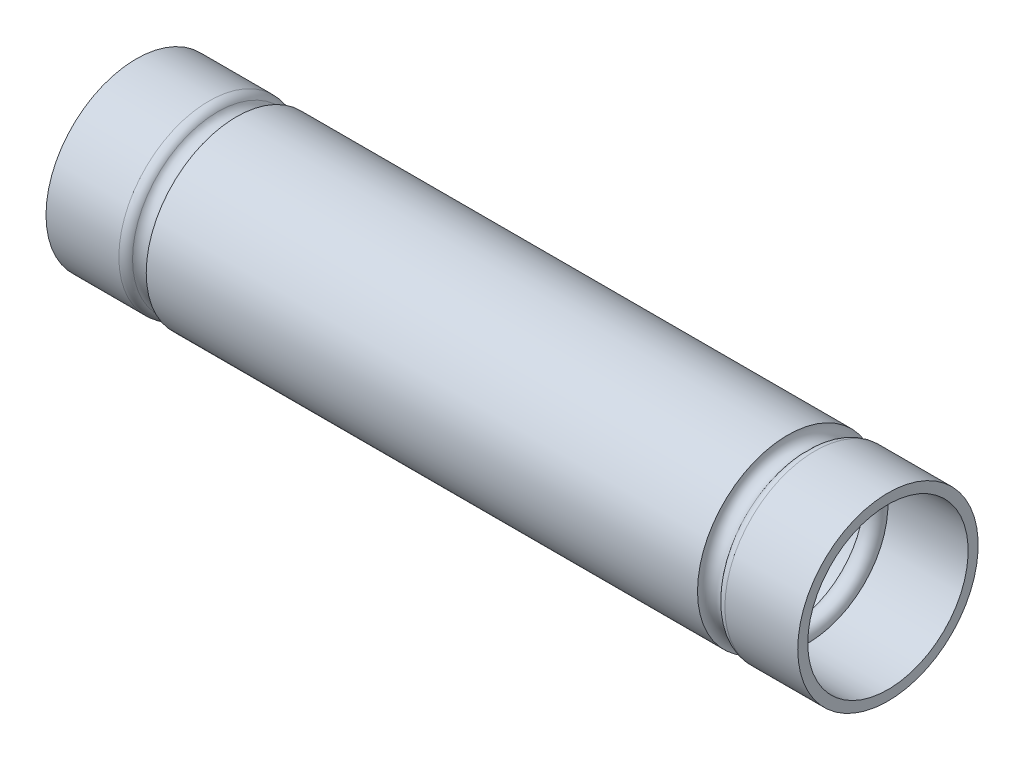
SolidWorks part; units mm, degrees
ref_plane "Front Plane" through (0, 0, 0) normal (0, 0, 1) x (1, 0, 0)
ref_plane "Top Plane" through (0, 0, 0) normal (0, 1, 0) x (1, 0, 0)
ref_plane "Right Plane" through (0, 0, 0) normal (1, 0, 0) x (0, 0, -1)
ref_plane "Plane1" through (0, 0, 0) normal (0, 0, -1) x (-1, 0, 0)
sketch "Sketch1" plane through (0, 0, 0) normal (0, 0, -1) x (-1, 0, 0)
  line L1 (-4, 4) -> (0, 4)
  line L2 (0, 4) -> (0, 4.5)
  line L3 (0, 4.5) -> (-4, 4.5)
  line L4 (-5, 4.5) -> (-32.5, 4.5)
  line L5 (-33.5, 4.5) -> (-37.5, 4.5)
  line L6 (-37.5, 4.5) -> (-37.5, 4)
  line L8 (-37.5, 0) -> (0, 0) construction
  line L9 (-37.5, 4) -> (-33.5, 4)
  line L10 (-32.5, 4) -> (-5, 4)
  arc A0 (-33.5, 4) -> (-32.5, 4) centre (-33, 4) ccw
  arc A1 (-5, 4) -> (-4, 4) centre (-4.5, 4) ccw
  arc A2 (-4, 4.5) -> (-5, 4.5) centre (-4.5, 4.5) cw
  arc A3 (-32.5, 4.5) -> (-33.5, 4.5) centre (-33, 4.5) cw
  point P18 (0, 0)
  point P19 (0, 0)
  point P20 (0, 0)
  point P21 (0, 0)
  point P23 (0, 0)
  dimension "D1" = 0.5
  dimension "D2" = 4.5
  dimension "D3" = 37.5
  dimension "D4" = 4.5
revolve "Revolve1" add sketch "Sketch1" angle 360 about L8
fillet "Fillet1" radius 0.5 2 edges at (33.5, 0, 4.5) (4, 0, 4.5)
